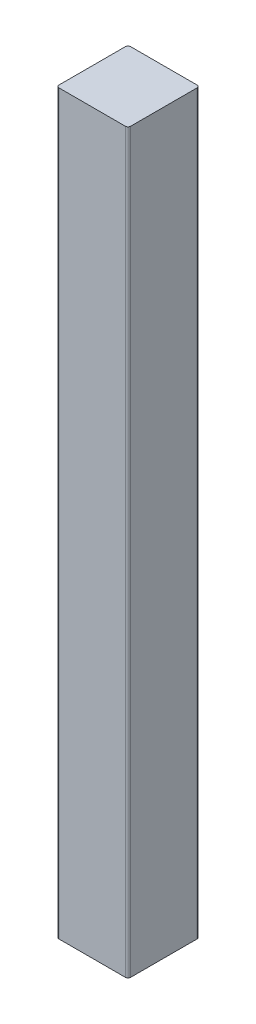
SolidWorks part; units mm, degrees
material "Pine"
ref_plane "Front Plane" through (0, 0, 0) normal (0, 0, 1) x (1, 0, 0)
ref_plane "Top Plane" through (0, 0, 0) normal (0, 1, 0) x (1, 0, 0)
ref_plane "Right Plane" through (0, 0, 0) normal (1, 0, 0) x (0, 0, -1)
sketch "Sketch1" plane through (0, 0, 0) normal (0, 1, 0) x (1, 0, 0)
  line L1 (-44.45, 44.45) -> (44.45, 44.45)
  line L2 (-44.45, 44.45) -> (-44.45, -44.45)
  line L3 (-44.45, -44.45) -> (44.45, -44.45)
  line L4 (44.45, 44.45) -> (44.45, -44.45)
  line L5 (-44.45, 44.45) -> (44.45, -44.45) construction
  line L6 (-44.45, -44.45) -> (44.45, 44.45) construction
  point P0 (0, 0)
  dimension "D1" = 88.9
extrude "Boss-Extrude1" add sketch "Sketch1" along normal blind 915.9875
fillet "Fillet1" radius 3.175 4 edges at (-44.45, 457.9937, 44.45) (-44.45, 457.9937, -44.45) (44.45, 457.9937, -44.45) (44.45, 457.9937, 44.45)
